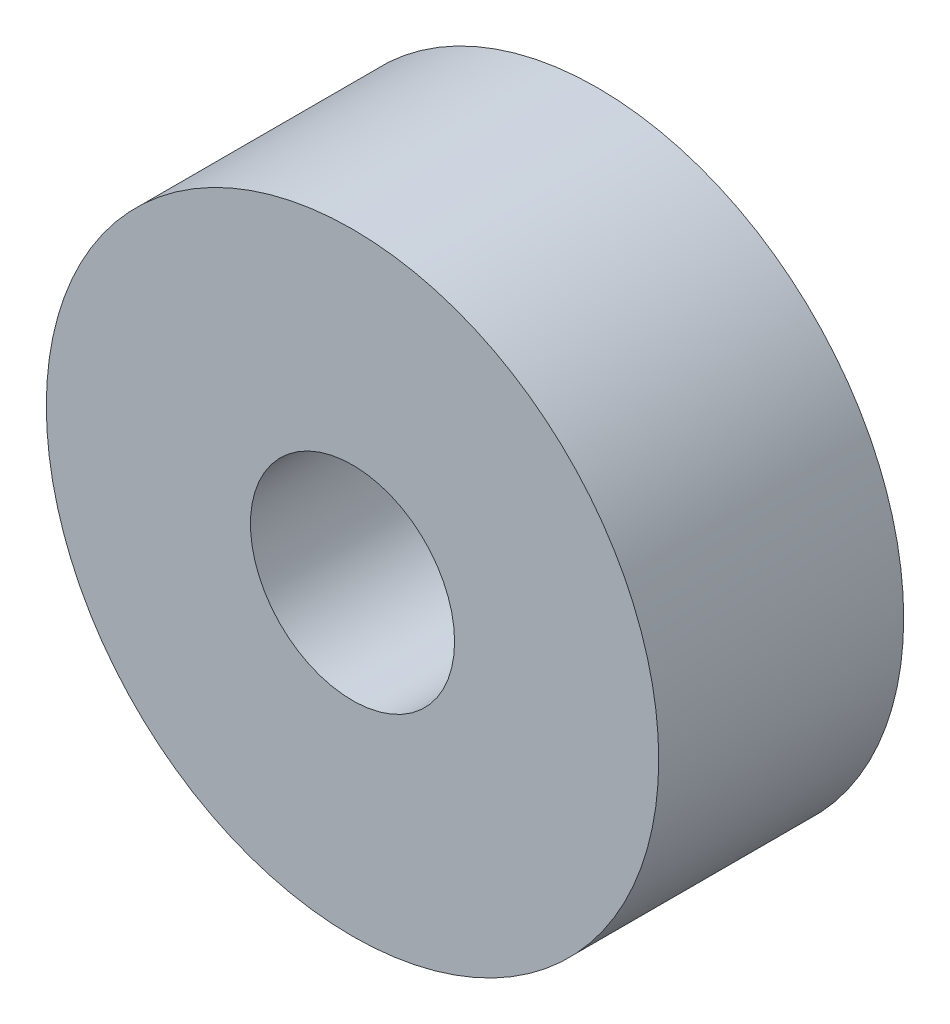
SolidWorks part; units mm, degrees
ref_plane "Front Plane" through (0, 0, 0) normal (0, 0, 1) x (1, 0, 0)
ref_plane "Top Plane" through (0, 0, 0) normal (0, 1, 0) x (1, 0, 0)
ref_plane "Right Plane" through (0, 0, 0) normal (1, 0, 0) x (0, 0, -1)
sketch "Sketch1" plane through (0, 0, 0) normal (0, 0, 1) x (1, 0, 0)
  circle A0 centre (0, 0) radius 75
  dimension "D1" = 150
extrude "Boss-Extrude1" add sketch "Sketch1" along normal blind 60
sketch "Sketch2" plane through (0, 0, 60) normal (0, 0, 1) x (1, 0, 0)
  circle A0 centre (0, 0) radius 25
  dimension "D1" = 50
extrude "Cut-Extrude1" cut sketch "Sketch2" against normal blind 50
